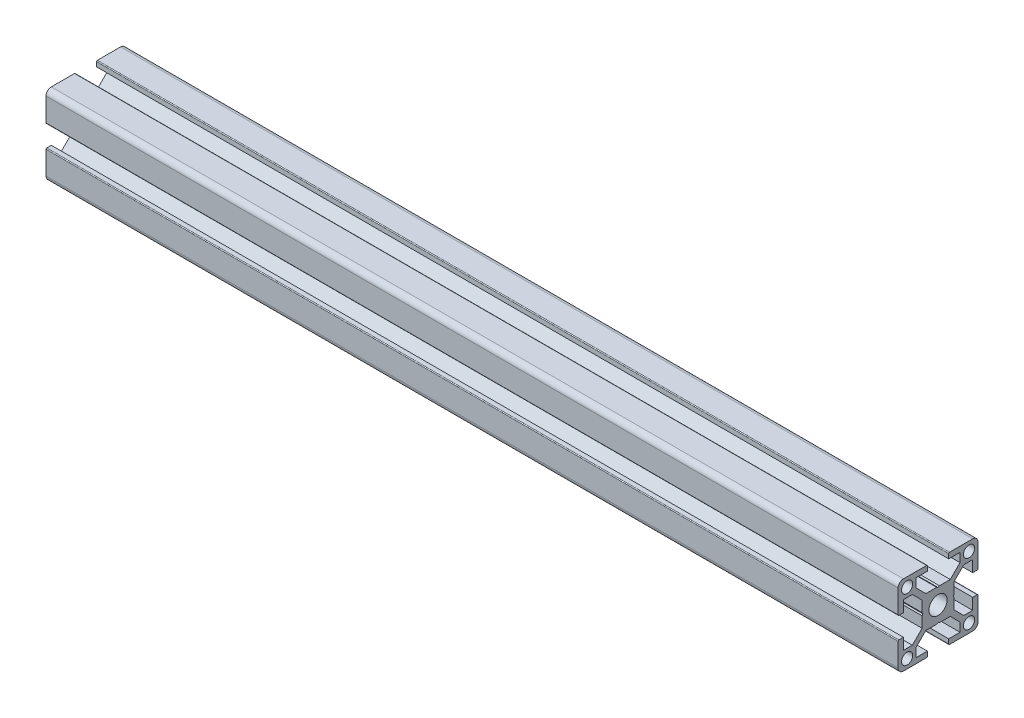
SolidWorks part; units mm, degrees
ref_plane "Front Plane" through (0, 0, 0) normal (0, 0, 1) x (1, 0, 0)
ref_plane "Top Plane" through (0, 0, 0) normal (0, 1, 0) x (1, 0, 0)
ref_plane "Right Plane" through (0, 0, 0) normal (1, 0, 0) x (0, 0, -1)
sketch "Sketch1" plane through (0, 0, 0) normal (0, 0, 1) x (1, 0, 0)
  line L0 (0, 0) -> (320, 0)
  dimension "D1" = 320
other "30xs6 30X30S6(1)"
ref_plane "Plane1" through (0, 0, 0) normal (1, 0, 0) x (0, 1, 0)
sketch "草图1" plane through (0, 0, 0) normal (1, 0, 0) x (0, 1, 0)
  line L0 (-14.7, 4) -> (-13, 4)
  line L1 (-13, 4) -> (-13, 8.25)
  line L2 (-13, 8.25) -> (-9.6642, 8.25)
  line L3 (-9.6642, 8.25) -> (-6, 4.5858)
  line L4 (-6, 4.5858) -> (-6, 0.5196)
  line L5 (-6, 0.5196) -> (-5.7, 0)
  line L6 (-5.7, 0) -> (-6, -0.5196)
  line L7 (-6, -0.5196) -> (-6, -4.5858)
  line L8 (-6, -4.5858) -> (-9.6642, -8.25)
  line L9 (-9.6642, -8.25) -> (-13, -8.25)
  line L10 (-13, -8.25) -> (-13, -4)
  line L11 (-13, -4) -> (-14.7, -4)
  line L12 (-15, -4.3) -> (-15, -13)
  line L13 (-13, -15) -> (-4.3, -15)
  line L14 (-4, -14.7) -> (-4, -13)
  line L15 (-4, -13) -> (-8.25, -13)
  line L16 (-8.25, -13) -> (-8.25, -9.6642)
  line L17 (-8.25, -9.6642) -> (-4.5858, -6)
  line L18 (-4.5858, -6) -> (-0.5196, -6)
  line L19 (-0.5196, -6) -> (0, -5.7)
  line L20 (0, -5.7) -> (0.5196, -6)
  line L21 (0.5196, -6) -> (4.5858, -6)
  line L22 (4.5858, -6) -> (8.25, -9.6642)
  line L23 (8.25, -9.6642) -> (8.25, -13)
  line L24 (8.25, -13) -> (4, -13)
  line L25 (4, -13) -> (4, -14.7)
  line L26 (4.3, -15) -> (13, -15)
  line L27 (15, -13) -> (15, -4.3)
  line L28 (14.7, -4) -> (13, -4)
  line L29 (13, -4) -> (13, -8.25)
  line L30 (13, -8.25) -> (9.6642, -8.25)
  line L31 (9.6642, -8.25) -> (6, -4.5858)
  line L32 (6, -4.5858) -> (6, -0.5196)
  line L33 (6, -0.5196) -> (5.7, 0)
  line L34 (5.7, 0) -> (6, 0.5196)
  line L35 (6, 0.5196) -> (6, 4.5858)
  line L36 (6, 4.5858) -> (9.6642, 8.25)
  line L37 (9.6642, 8.25) -> (13, 8.25)
  line L38 (13, 8.25) -> (13, 4)
  line L39 (13, 4) -> (14.7, 4)
  line L40 (15, 4.3) -> (15, 13)
  line L41 (13, 15) -> (4.3, 15)
  line L42 (4, 14.7) -> (4, 13)
  line L43 (4, 13) -> (8.25, 13)
  line L44 (8.25, 13) -> (8.25, 9.6642)
  line L45 (8.25, 9.6642) -> (4.5858, 6)
  line L46 (4.5858, 6) -> (0.5196, 6)
  line L47 (0.5196, 6) -> (0, 5.7)
  line L48 (0, 5.7) -> (-0.5196, 6)
  line L49 (-0.5196, 6) -> (-4.5858, 6)
  line L50 (-4.5858, 6) -> (-8.25, 9.6642)
  line L51 (-8.25, 9.6642) -> (-8.25, 13)
  line L52 (-8.25, 13) -> (-4, 13)
  line L53 (-4, 13) -> (-4, 14.7)
  line L54 (-4.3, 15) -> (-13, 15)
  line L55 (-15, 13) -> (-15, 4.3)
  arc A0 (-15, 4.3) -> (-14.7, 4) centre (-14.7, 4.3) ccw
  arc A1 (-14.7, -4) -> (-15, -4.3) centre (-14.7, -4.3) ccw
  arc A2 (-15, -13) -> (-13, -15) centre (-13, -13) ccw
  arc A3 (-4.3, -15) -> (-4, -14.7) centre (-4.3, -14.7) ccw
  arc A4 (4, -14.7) -> (4.3, -15) centre (4.3, -14.7) ccw
  arc A5 (13, -15) -> (15, -13) centre (13, -13) ccw
  arc A6 (15, -4.3) -> (14.7, -4) centre (14.7, -4.3) ccw
  arc A7 (14.7, 4) -> (15, 4.3) centre (14.7, 4.3) ccw
  arc A8 (15, 13) -> (13, 15) centre (13, 13) ccw
  arc A9 (4.3, 15) -> (4, 14.7) centre (4.3, 14.7) ccw
  arc A10 (-4, 14.7) -> (-4.3, 15) centre (-4.3, 14.7) ccw
  arc A11 (-13, 15) -> (-15, 13) centre (-13, 13) ccw
  circle A12 centre (11.625, 11.625) radius 2.1
  circle A13 centre (11.625, -11.625) radius 2.1
  circle A14 centre (0, 0) radius 3.4
  circle A15 centre (-11.625, -11.625) radius 2.1
  circle A16 centre (-11.625, 11.625) radius 2.1
  point P90 (-15, 15)
  point P91 (-0.2598, 14.9121)
  point P92 (15, 15)
  point P93 (15, 0)
  point P94 (15, -15)
  point P95 (0.2598, -15)
  point P96 (-15, -15)
  point P97 (-15, 0)
  point P98 (0, 0)
